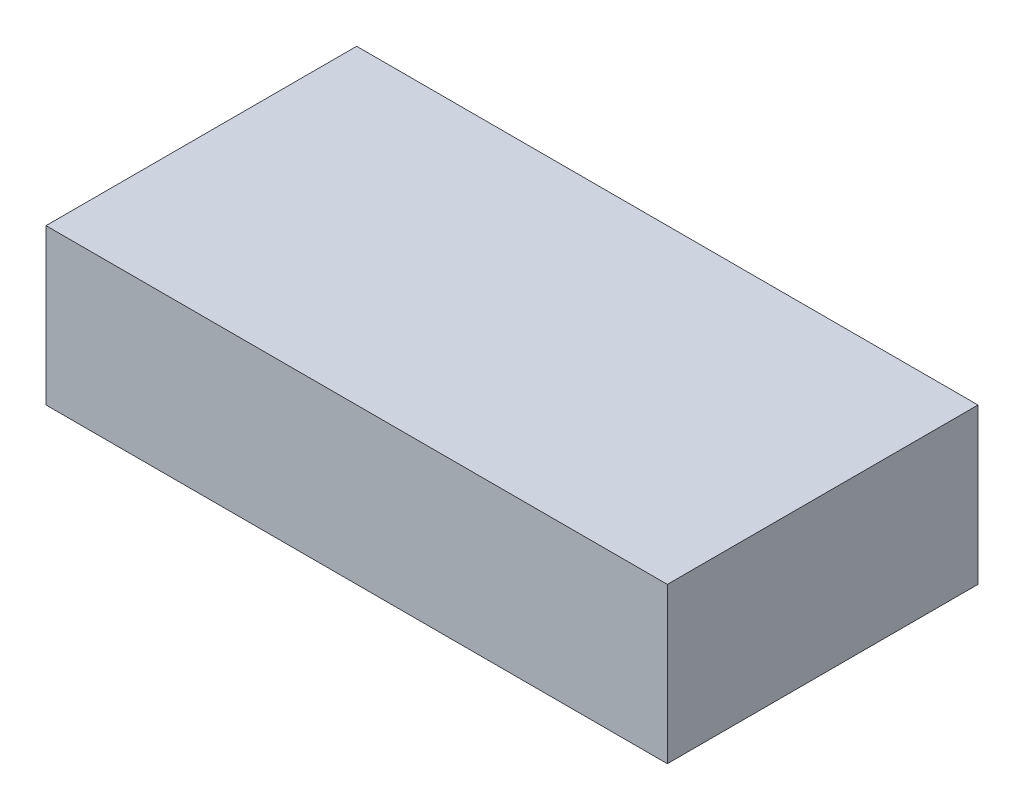
SolidWorks part; units mm, degrees
ref_plane "Front Plane" through (0, 0, 0) normal (0, 0, 1) x (1, 0, 0)
ref_plane "Top Plane" through (0, 0, 0) normal (0, 1, 0) x (1, 0, 0)
ref_plane "Right Plane" through (0, 0, 0) normal (1, 0, 0) x (0, 0, -1)
sketch "Sketch1" plane through (0, 0, 0) normal (0, 1, 0) x (1, 0, 0)
  line L1 (0, 0) -> (40, 0)
  line L2 (0, 0) -> (0, 20)
  line L3 (0, 20) -> (40, 20)
  line L4 (40, 0) -> (40, 20)
extrude "Boss-Extrude1" add sketch "Sketch1" against normal blind 10
